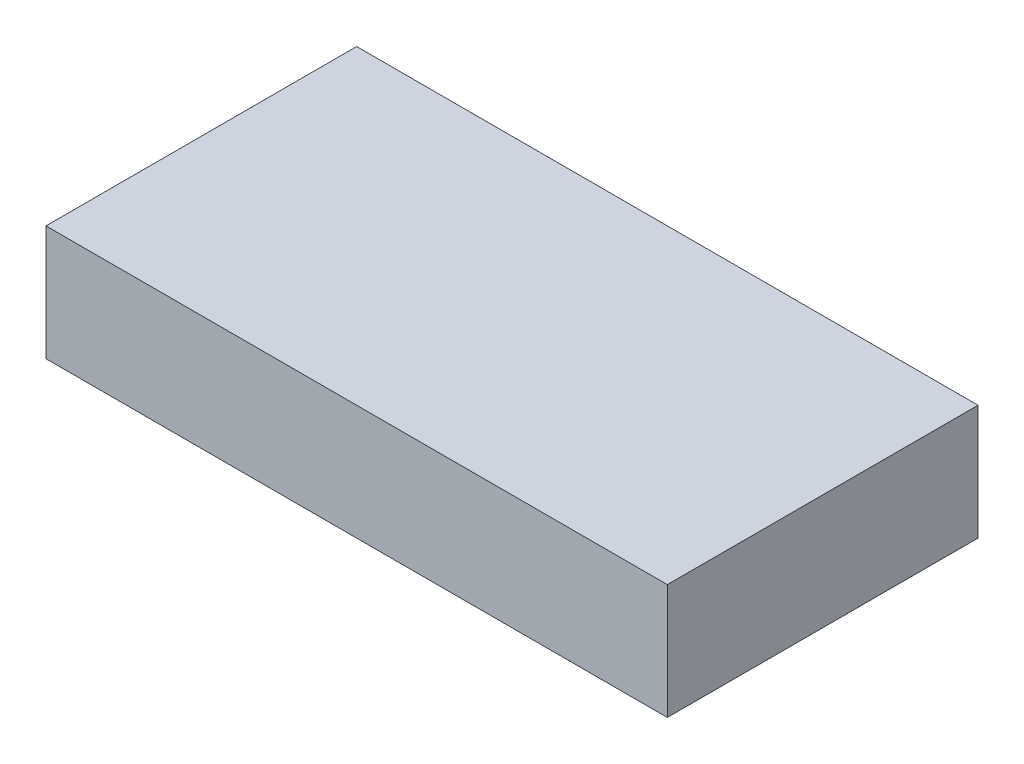
SolidWorks part; units mm, degrees
ref_plane "Front Plane" through (0, 0, 0) normal (0, 0, 1) x (1, 0, 0)
ref_plane "Top Plane" through (0, 0, 0) normal (0, 1, 0) x (1, 0, 0)
ref_plane "Right Plane" through (0, 0, 0) normal (1, 0, 0) x (0, 0, -1)
sketch "Sketch2" plane through (0, 0, 0) normal (0, 1, 0) x (1, 0, 0)
  line L1 (0, 0) -> (48, 0)
  line L2 (0, 0) -> (0, 24)
  line L3 (0, 24) -> (48, 24)
  line L4 (48, 0) -> (48, 24)
  dimension "D1" = 48
  dimension "D2" = 24
extrude "Boss-Extrude1" add sketch "Sketch2" along normal blind 8.89
